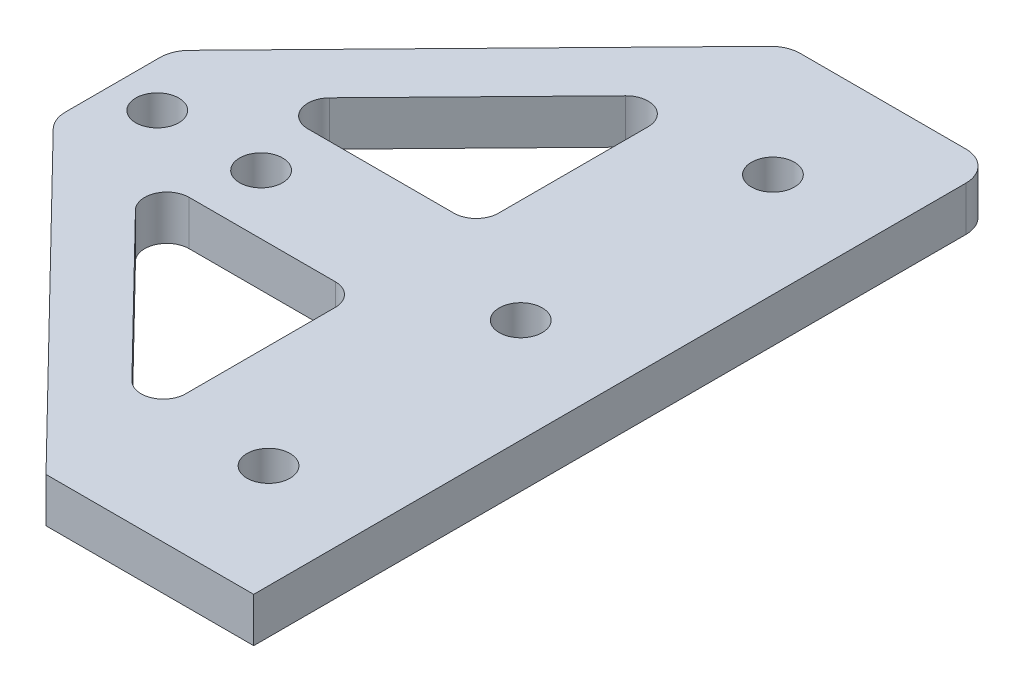
SolidWorks part; units mm, degrees
material "Thornel Mat VMA"
ref_plane "前视基准面" through (0, 0, 0) normal (0, 0, 1) x (1, 0, 0)
ref_plane "上视基准面" through (0, 0, 0) normal (0, 1, 0) x (1, 0, 0)
ref_plane "右视基准面" through (0, 0, 0) normal (1, 0, 0) x (0, 0, -1)
other "Configuration Table"
sketch "草图1" plane through (0, 0, 0) normal (0, 1, 0) x (1, 0, 0)
  line L0 (0, 4) -> (27.5, 4) construction
  line L1 (0, 0) -> (27.5, 0)
  line L2 (0, 0) -> (0, 8)
  line L3 (0, 8) -> (27.5, 8)
  line L4 (27.5, 0) -> (27.5, 8)
  line L5 (27.5, 4) -> (39.5341, 37.0633)
  circle A0 centre (3, 4) radius 1.45
  circle A1 centre (10, 4) radius 1.45
  dimension "D1" = 2.9
  dimension "D2" = 2.9
  dimension "D3" = 7
  dimension "D4" = 3
  dimension "D5" = 8
  dimension "D6" = 17.5
  dimension "D7" = 110
extrude "凸台-拉伸1" add sketch "草图1" along normal blind 3 contours L2 L0 A0 A1 L4 L3 | L0 L2 L1 L4 A1 A0
sketch "草图2" plane through (0, 3, 0) normal (0, 1, 0) x (1, 0, 0)
  line L0 (27.5, 4) -> (0, 4) construction
  line L1 (27.5, 0) -> (27.5, 8) construction
  line L2 (0, 0) -> (0, 8) construction
  line L3 (27.5, -21) -> (27.5, 29) construction
  line L4 (34.5, -21) -> (34.5, 29)
  line L5 (20.5, -21) -> (20.5, 29)
  line L6 (20.5, -21) -> (34.5, -21)
  line L7 (20.5, 29) -> (34.5, 29)
  dimension "D1" = 90
  dimension "D2" = 50
  dimension "D3" = 7
  dimension "D4" = 7
extrude "凸台-拉伸2" add sketch "草图2" against normal blind 3
sketch "草图3" plane through (0, 3, 0) normal (0, 1, 0) x (1, 0, 0)
  line L0 (27.5, -21) -> (27.5, 29) construction
  line L1 (20.5, -21) -> (34.5, -21) construction
  line L2 (34.5, 29) -> (20.5, 29) construction
  circle A0 centre (27.5, 21) radius 1.45
  circle A1 centre (27.5, 4) radius 1.45
  circle A2 centre (27.5, -13) radius 1.45
  dimension "D1" = 2.9
  dimension "D2" = 2.9
  dimension "D3" = 2.9
  dimension "D4" = 17
  dimension "D5" = 17
extrude "切除-拉伸1" cut sketch "草图3" against normal through all
sketch "草图4" plane through (0, 3, 0) normal (0, 1, 0) x (1, 0, 0)
  line L0 (0, 8) -> (20.5, 29)
  line L1 (20.5, 29) -> (20.5, 23.2737)
  line L2 (20.5, 29) -> (20.5, 8) construction
  line L3 (20.5, 23.2737) -> (5.5899, 8)
  line L4 (0, 8) -> (20.5, 8) construction
  line L5 (5.5899, 8) -> (0, 8)
  line L6 (20.5, -21) -> (0, 0)
  line L7 (0, 0) -> (5.5899, 0)
  line L8 (0, 0) -> (20.5, 0) construction
  line L9 (5.5899, 0) -> (20.5, -15.2737)
  line L10 (5.5899, 8) -> (5.5899, 0) construction
  line L11 (20.5, -15.2737) -> (20.5, -21)
  line L12 (20.5, 0) -> (20.5, -21) construction
  line L13 (20.5, -21) -> (34.5, -21) construction
  dimension "D1" = 4
extrude "凸台-拉伸3" add sketch "草图4" against normal blind 3
fillet "圆角1" radius 1.5 6 edges at (20.5, 1.5, -23.2737) (20.5, 1.5, -8) (20.5, 1.5, 0) (20.5, 1.5, 15.2737) (5.5899, 1.5, 0) (5.5899, 1.5, -8)
fillet "圆角2" radius 2 4 edges at (34.5, 1.5, -29) (20.5, 1.5, -29) (0, 1.5, -8) (0, 1.5, 0)
